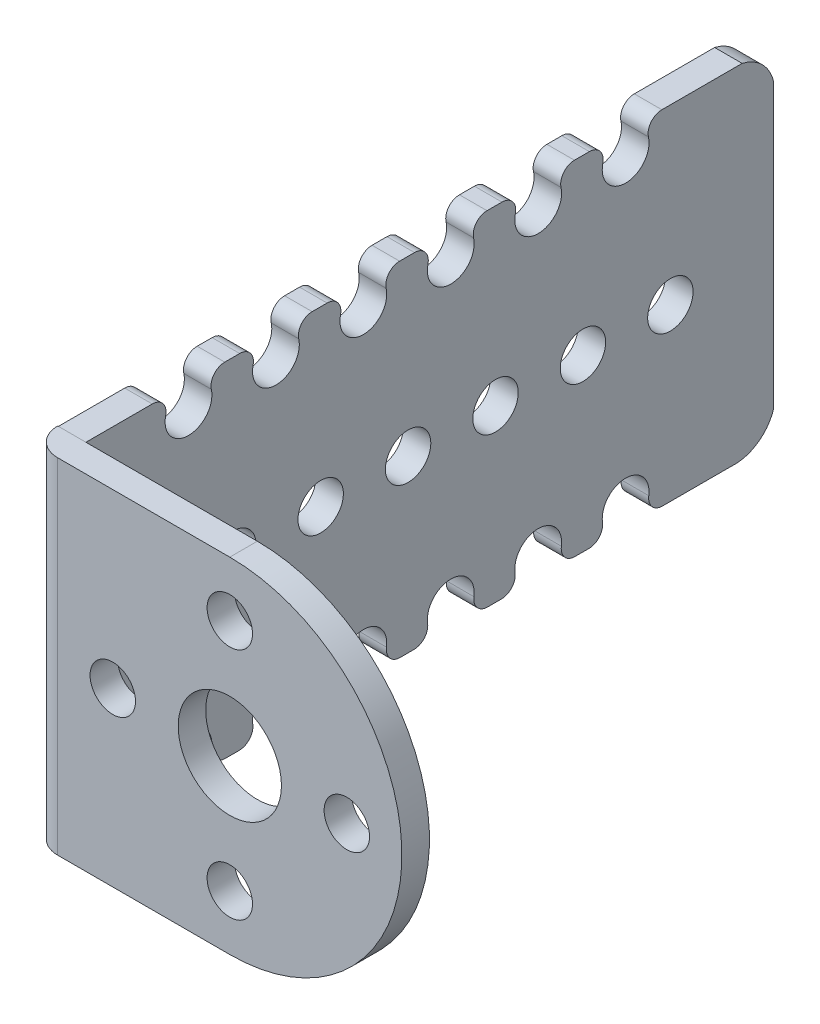
SolidWorks part; units mm, degrees
ref_plane "Alzado" through (0, 0, 0) normal (0, 0, 1) x (1, 0, 0)
ref_plane "Planta" through (0, 0, 0) normal (0, 1, 0) x (1, 0, 0)
ref_plane "Vista lateral" through (0, 0, 0) normal (1, 0, 0) x (0, 0, -1)
sketch "Croquis1" plane through (0, 0, 0) normal (0, 0, 1) x (1, 0, 0)
  line L0 (0, 0) -> (0, 25)
  line L1 (0, 0) -> (14.5, 0)
  line L2 (0, 25) -> (14.5, 25)
  line L3 (0, 12.5) -> (14.5, 12.5) construction
  line L4 (14.5, 12.5) -> (14.5, 25) construction
  line L5 (0, 12.5) -> (27, 12.5) construction
  circle A0 centre (14.5, 12.5) radius 3.75
  circle A1 centre (14.5, 21) radius 1.65
  circle A2 centre (23, 12.5) radius 1.65
  circle A3 centre (14.5, 4) radius 1.65
  circle A4 centre (6, 12.5) radius 1.65
  arc A5 (14.5, 25) -> (14.5, 0) centre (14.5, 12.5) cw
  dimension "D1" = 25
  dimension "D2" = 14.5
  dimension "D3" = 7.5
  dimension "D4" = 3.3
  dimension "D5" = 3.3
  dimension "D6" = 3.3
  dimension "D7" = 3.3
  dimension "D8" = 27
extrude "Saliente-Extruir1" add sketch "Croquis1" along normal blind 2
sketch "Croquis4" plane through (0, 0, 0) normal (-1, 0, 0) x (0, 0, 1)
  line L0 (-45.3169, 24.95) -> (-45.3169, 0) construction
  line L1 (2, 0) -> (-46.9228, 0)
  line L2 (2, 0) -> (2, 24.95)
  line L3 (2, 24.95) -> (-47.7155, 24.95)
  line L4 (-50, 2.0772) -> (-50, 22.6655)
  arc A0 (-47.7155, 24.95) -> (-50, 22.6655) centre (-47.0162, 21.9662) ccw
  arc A1 (-46.9228, 0) -> (-50, 2.0772) centre (-47.15, 2.9813) cw
  dimension "D1" = 52
extrude "Saliente-Extruir2" add sketch "Croquis4" against normal blind 2
sketch "Croquis5" plane through (2, 0, 0) normal (1, 0, 0) x (0, 0, -1)
  line L0 (50, 12.3713) -> (42.5, 12.3713) construction
  line L1 (50, 22.6655) -> (50, 2.0772) construction
  line L2 (42.5, 12.3713) -> (36.15, 12.3713) construction
  line L3 (36.15, 12.3713) -> (29.8, 12.3713) construction
  line L4 (29.8, 12.3713) -> (23.45, 12.3713) construction
  line L5 (23.45, 12.3713) -> (17.1, 12.3713) construction
  line L6 (17.1, 12.3713) -> (10.75, 12.3713) construction
  line L7 (10.75, 12.3713) -> (4.4, 12.3713) construction
  line L8 (7.5, 23.35) -> (13.85, 23.35) construction
  line L9 (-2, 25) -> (-2, 0) construction
  line L11 (-2, 12.5) -> (-2, 23.35) construction
  line L12 (-2, 25) -> (-2, 0) construction
  line L13 (-2, 12.5) -> (-2, 1.65) construction
  line L14 (-2, 23.35) -> (7.5, 23.35) construction
  line L15 (13.85, 23.35) -> (20.2, 23.35) construction
  line L16 (20.2, 23.35) -> (26.55, 23.35) construction
  line L17 (26.55, 23.35) -> (32.9, 23.35) construction
  line L18 (32.9, 23.35) -> (39.25, 23.35) construction
  line L19 (39.25, 23.35) -> (45.45, 23.35) construction
  circle A0 centre (42.5, 12.3713) radius 1.65
  circle A1 centre (36.15, 12.3713) radius 1.65
  circle A2 centre (29.8, 12.3713) radius 1.65
  circle A3 centre (23.45, 12.3713) radius 1.65
  circle A4 centre (17.1, 12.3713) radius 1.65
  circle A5 centre (10.75, 12.3713) radius 1.65
  circle A6 centre (4.4, 12.3713) radius 1.65
  circle A7 centre (7.5, 23.35) radius 1.7
  circle A8 centre (13.85, 23.35) radius 1.7
  circle A9 centre (20.2, 23.35) radius 1.7
  circle A10 centre (26.55, 23.35) radius 1.7
  circle A11 centre (32.9, 23.35) radius 1.7
  circle A12 centre (39.25, 23.35) radius 1.7
  circle A16 centre (39.25, 1.3927) radius 1.7
  circle A17 centre (32.9, 1.3927) radius 1.7
  circle A18 centre (26.55, 1.3927) radius 1.7
  circle A19 centre (20.2, 1.3927) radius 1.7
  circle A20 centre (13.85, 1.3927) radius 1.7
  circle A21 centre (7.5, 1.3927) radius 1.7
  dimension "D2" = 3.3
  dimension "D4" = 6.35
  dimension "D6" = 3.3
  dimension "D7" = 3.3
  dimension "D8" = 3.3
  dimension "D12" = 3.3
  dimension "D13" = 3.3
  dimension "D14" = 3.3
  dimension "D18" = 3.4
  dimension "D20" = 3.4
  dimension "D23" = 6.35
  dimension "D25" = 3.4
  dimension "D26" = 3.4
  dimension "D27" = 3.4
  dimension "D28" = 3.4
  dimension "D31" = 6.4
  dimension "D3" = 6.35
  dimension "D5" = 6.35
  dimension "D9" = 6.35
  dimension "D10" = 6.35
  dimension "D11" = 6.35
  dimension "D15" = 9.5
  dimension "D16" = 10.85
  dimension "D17" = 10.85
  dimension "D19" = 6.35
  dimension "D21" = 6.35
  dimension "D22" = 6.2
  dimension "D24" = 6.35
  dimension "D30" = 6.35
extrude "Cortar-Extruir2" cut sketch "Croquis5" against normal blind 10
fillet "Redondeo3" radius 1 2 edges at (1, 24.95, -13.2756) (1, 24.95, -8.0744)
fillet "Redondeo4" radius 1 4 edges at (1, 24.95, -25.9756) (1, 24.95, -19.6256) (1, 24.95, -20.7744) (1, 24.95, -14.4244)
fillet "Redondeo5" radius 1 5 edges at (1, 24.95, -38.6756) (1, 24.95, -39.8244) (1, 24.95, -32.3256) (1, 24.95, -33.4744) (1, 24.95, -27.1244)
fillet "Redondeo6" radius 1 1 edges at (1, 24.95, -6.9256)
fillet "Redondeo7" radius 1 9 edges at (1, 0, -31.9251) (1, 0, -27.5249) (1, 0, -25.5751) (1, 0, -21.1749) (1, 0, -19.2251) (1, 0, -14.8249) (1, 0, -12.8751) (1, 0, -8.4749) (1, 0, -6.5251)
fillet "Redondeo8" radius 1 3 edges at (1, 0, -40.2249) (1, 0, -38.2751) (1, 0, -33.8749)
fillet "Redondeo12" radius 2 1 edges at (0, 12.5, 2)
